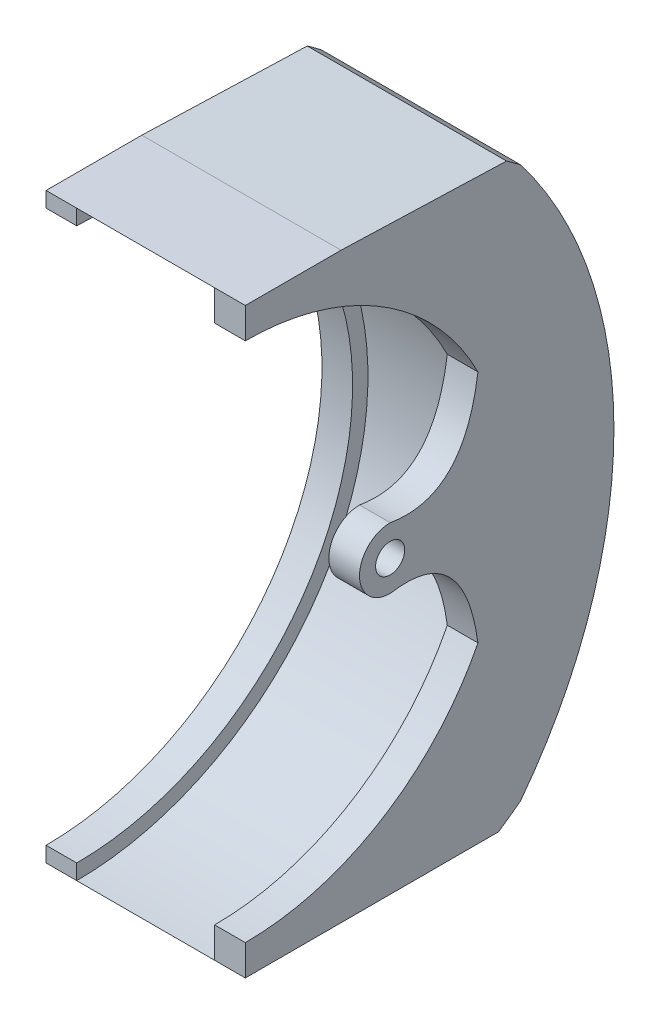
SolidWorks part; units mm, degrees
ref_plane "Plan de face" through (0, 0, 0) normal (0, 0, 1) x (1, 0, 0)
ref_plane "Plan de dessus" through (0, 0, 0) normal (0, 1, 0) x (1, 0, 0)
ref_plane "Plan de droite" through (0, 0, 0) normal (1, 0, 0) x (0, 0, -1)
sketch "Esquisse1" plane through (0, 0, 0) normal (1, 0, 0) x (0, 0, -1)
  line L0 (17.9753, 17.9475) -> (17.9753, -17.9475) construction
  line L1 (14.1443, 14.14) -> (14.1443, -14.14) construction
  line L2 (0, 3.9479) -> (0, -6.61) construction
  line L3 (14.1443, 14.14) -> (17.9753, 17.9475)
  line L4 (14.1443, -14.14) -> (17.9753, -17.9475)
  circle A0 centre (0, 0) radius 20 construction
  circle A1 centre (-5.5, 0) radius 29.55 construction
  arc A2 (14.1443, 14.14) -> (14.1443, -14.14) centre (0, 0) cw
  arc A3 (17.9753, 17.9475) -> (17.9753, -17.9475) centre (-5.5, 0) cw
  dimension "D1" = 40
  dimension "D2" = 59.1
  dimension "D5" = 35.8949
  dimension "D3" = 0
  dimension "D4" = 5.5
  dimension "D6" = 28.28
extrude "Boss.-Extru.1" add sketch "Esquisse1" along normal blind 114
sketch "Esquisse2" plane through (0, 0, 0) normal (-1, 0, 0) x (0, 0, 1)
  circle A0 centre (0, 0) radius 22.55
  dimension "D1" = 45.1
extrude "Enlèv. mat.-Extru.2" cut sketch "Esquisse2" against normal blind 5
sketch "Esquisse4" plane through (114, 0, 0) normal (1, 0, 0) x (0, 0, -1)
  circle A0 centre (0, 0) radius 22.55
  dimension "D1" = 45.1
extrude "Enlèv. mat.-Extru.3" cut sketch "Esquisse4" against normal blind 5
sketch "Esquisse5" plane through (0, 0, 0) normal (0, 0, 1) x (1, 0, 0)
  line L0 (0, 15.9376) -> (0, -15.9376) construction
  line L1 (114, -15.9376) -> (114, 15.9376) construction
  circle A0 centre (2.5, 0) radius 1
  circle A1 centre (111.5, 0) radius 1
  dimension "D1" = 2
  dimension "D2" = 2
  dimension "D3" = 0
  dimension "D4" = 0
  dimension "D5" = 2.5
  dimension "D6" = 2.5
extrude "Enlèv. mat.-Extru.4" cut sketch "Esquisse5" against normal through all
ref_plane "Plan1" through (88.7, 0, 0) normal (1, 0, 0) x (0, 0, -1)
sketch "Esquisse6" plane through (88.7, 0, 0) normal (1, 0, 0) x (0, 0, -1)
  line L0 (0, 17) -> (0, 20)
  line L1 (0, -17) -> (0, -20)
  arc A0 (0, -17) -> (0, 17) centre (0, 0) ccw
  arc A1 (0, -20) -> (0, 20) centre (0, 0) ccw
  dimension "D1" = 34
extrude "Boss.-Extru.2" add sketch "Esquisse6" against normal blind 2
sketch "Esquisse7" plane through (86.7, 0, 0) normal (-1, 0, 0) x (0, 0, 1)
  line L0 (0, 20) -> (0, 19)
  line L1 (0, -20) -> (0, -19)
  arc A0 (0, 19) -> (0, -19) centre (0, 0) ccw
  arc A1 (0, 20) -> (0, -20) centre (0, 0) ccw
  dimension "D1" = 38
extrude "Boss.-Extru.3" add sketch "Esquisse7" along normal blind 9
sketch "Esquisse8" plane through (77.7, 0, 0) normal (-1, 0, 0) x (0, 0, 1)
  line L0 (0, 20) -> (0, 18)
  line L1 (0, -20) -> (0, -18)
  arc A0 (0, 18) -> (0, -18) centre (0, 0) ccw
  arc A1 (0, 20) -> (0, -20) centre (0, 0) ccw
  dimension "D1" = 36
extrude "Boss.-Extru.4" add sketch "Esquisse8" along normal blind 2
ref_plane "Plan2" through (55.6, 0, 0) normal (1, 0, 0) x (0, 0, -1)
sketch "Esquisse9" plane through (55.6, 0, 0) normal (1, 0, 0) x (0, 0, -1)
  line L0 (0, 20) -> (0, 17)
  line L1 (0, -20) -> (0, -17)
  arc A0 (0, -17) -> (0, 17) centre (0, 0) ccw
  arc A1 (0, 20) -> (0, -20) centre (0, 0) cw
extrude "Boss.-Extru.5" add sketch "Esquisse9" against normal blind 2
sketch "Esquisse10" plane through (53.6, 0, 0) normal (-1, 0, 0) x (0, 0, 1)
  line L0 (0, 20) -> (0, 19)
  line L1 (0, -20) -> (0, -19)
  arc A0 (0, 19) -> (0, -19) centre (0, 0) ccw
  arc A1 (0, 20) -> (0, -20) centre (0, 0) ccw
  dimension "D1" = 38
extrude "Boss.-Extru.6" add sketch "Esquisse10" along normal blind 9
sketch "Esquisse11" plane through (44.6, 0, 0) normal (-1, 0, 0) x (0, 0, 1)
  line L0 (0, 20) -> (0, 18)
  line L1 (0, -20) -> (0, -18)
  arc A0 (0, 18) -> (0, -18) centre (0, 0) ccw
  arc A1 (0, 20) -> (0, -20) centre (0, 0) ccw
extrude "Boss.-Extru.7" add sketch "Esquisse11" along normal blind 2
sketch "Esquisse12" plane through (88.7, 0, 0) normal (1, 0, 0) x (0, 0, -1)
  line L1 (0, -20) -> (13.7518, -20)
  line L2 (0, -20) -> (0, -19)
  line L3 (0, -19) -> (13.7518, -19)
  line L4 (13.7518, -20) -> (13.7518, -19)
  line L5 (0, 20) -> (11.1675, 20)
  line L6 (0, 20) -> (0, 19)
  line L7 (0, 19) -> (11.1675, 19)
  line L8 (11.1675, 20) -> (11.1675, 19)
  dimension "D1" = 2
  dimension "D2" = 2
extrude "Enlèv. mat.-Extru.5" cut sketch "Esquisse12" against normal through all
sketch "Esquisse13" plane through (88.7, 0, 0) normal (1, 0, 0) x (0, 0, -1)
  line L1 (17.9753, 17.9475) -> (14.1443, 14.14)
  line L2 (14.1443, -14.14) -> (17.9753, -17.9475)
  line L4 (6.245, 19) -> (17.4397, 18.6272)
  line L5 (6.245, -19) -> (17.1319, -19)
  arc A0 (14.1443, 14.14) -> (6.245, 19) centre (0, 0) ccw
  arc A1 (6.245, -19) -> (14.1443, -14.14) centre (0, 0) ccw
  arc A2 (17.9753, 17.9475) -> (17.4397, 18.6272) centre (-5.5, 0) ccw
  arc A3 (17.9753, -17.9475) -> (17.1319, -19) centre (-5.5, 0) cw
extrude "Boss.-Extru.8" add sketch "Esquisse13" against normal up to surface (13 mm away) up to face at (75.7, 0, -8.1507)
sketch "Esquisse14" plane through (55.6, 0, 0) normal (1, 0, 0) x (0, 0, -1)
  line L0 (14.1443, 14.14) -> (17.9753, 17.9475)
  line L2 (14.1443, -14.14) -> (17.9753, -17.9475)
  line L4 (6.245, 19) -> (17.4397, 18.6272)
  line L5 (6.245, -19) -> (17.1319, -19)
  arc A0 (14.1443, 14.14) -> (6.245, 19) centre (0, 0) ccw
  arc A1 (14.1443, -14.14) -> (6.245, -19) centre (0, 0) cw
  arc A2 (17.4397, 18.6272) -> (17.9753, 17.9475) centre (-5.5, 0) cw
  arc A3 (17.9753, -17.9475) -> (17.1319, -19) centre (-5.5, 0) cw
extrude "Boss.-Extru.9" add sketch "Esquisse14" against normal up to surface (13 mm away) up to face at (42.6, 0, -8.1507)
sketch "Esquisse15" plane through (88.7, 0, 0) normal (1, 0, 0) x (0, 0, -1)
  line L0 (14.4093, 20.2987) -> (16.9015, 24.7608)
  line L1 (16.9015, 24.7608) -> (24.8905, 20.2987)
  line L2 (24.8905, 20.2987) -> (20.896, 15.394)
  line L3 (14.4093, -20.2987) -> (16.9015, -24.7608)
  line L4 (16.9015, -24.7608) -> (22.9342, -18.4643)
  line L5 (22.9342, -18.4643) -> (20.4311, -15.8488)
  arc A1 (14.4093, -20.2987) -> (20.4311, -15.8488) centre (0, 5.5) ccw
  arc A2 (20.896, 15.394) -> (14.4093, 20.2987) centre (0, -5.5) ccw
  dimension "D3" = 59.1
  dimension "D1" = 5.5
  dimension "D2" = 5.5
extrude "Enlèv. mat.-Extru.6" cut sketch "Esquisse15" against normal through all
sketch "Esquisse16" plane through (0, 0, 0) normal (0, 0, 1) x (1, 0, 0)
  line L0 (114, -15.9376) -> (114, 15.9376) construction
  circle A0 centre (114, 13) radius 2
  circle A1 centre (114, -13) radius 2
  circle A2 centre (111.5, 0) radius 1 construction
  dimension "D2" = 4
  dimension "D3" = 4
  dimension "D5" = 13
  dimension "D1" = 0
  dimension "D4" = 0
  dimension "D6" = 13
extrude "Enlèv. mat.-Extru.7" cut sketch "Esquisse16" against normal through all both and the other way through all
sketch "Esquisse17" plane through (0, 0, 0) normal (0, 0, 1) x (1, 0, 0)
  line L1 (42.6, 19) -> (-17.0148, 19)
  line L2 (42.6, 19) -> (42.6, -27.7843)
  line L3 (42.6, -27.7843) -> (-17.0148, -27.7843)
  line L4 (-17.0148, 19) -> (-17.0148, -27.7843)
  line L5 (55.6, 19) -> (118.6605, 19)
  line L6 (55.6, 19) -> (55.6, -28.2749)
  line L7 (55.6, -28.2749) -> (118.6605, -28.2749)
  line L8 (118.6605, 19) -> (118.6605, -28.2749)
extrude "Enlèv. mat.-Extru.8" cut sketch "Esquisse17" against normal through all both
sketch "Esquisse18" plane through (55.6, 0, 0) normal (1, 0, 0) x (0, 0, -1)
  line L0 (0, 0) -> (34.9854, 0) construction
  circle A0 centre (9.45, 0) radius 0.95
  arc A1 (0, -19) -> (0, 19) centre (0, 0) ccw construction
  arc A2 (9.45, 2) -> (9.45, -2) centre (9.45, 0) ccw
  arc A3 (0, -17) -> (0, 17) centre (0, 0) ccw construction
  arc A4 (15.1786, 7.6556) -> (15.1786, -7.6556) centre (0, 0) cw
  spline S0 degree 2 poles (9.45, 2) (14.2867, 1.1651) (15.1786, 7.6556) knots 0 0 0 1 1 1
  spline S1 degree 2 poles (9.45, -2) (14.2867, -1.1651) (15.1786, -7.6556) knots 0 0 0 1 1 1
  dimension "D1" = 1.9
  dimension "D2" = 9.45
  dimension "D4" = 4
  dimension "D3" = 0
extrude "Boss.-Extru.10" add sketch "Esquisse18" against normal up to surface (2 mm away) up to face at (53.6, 0, -9)
